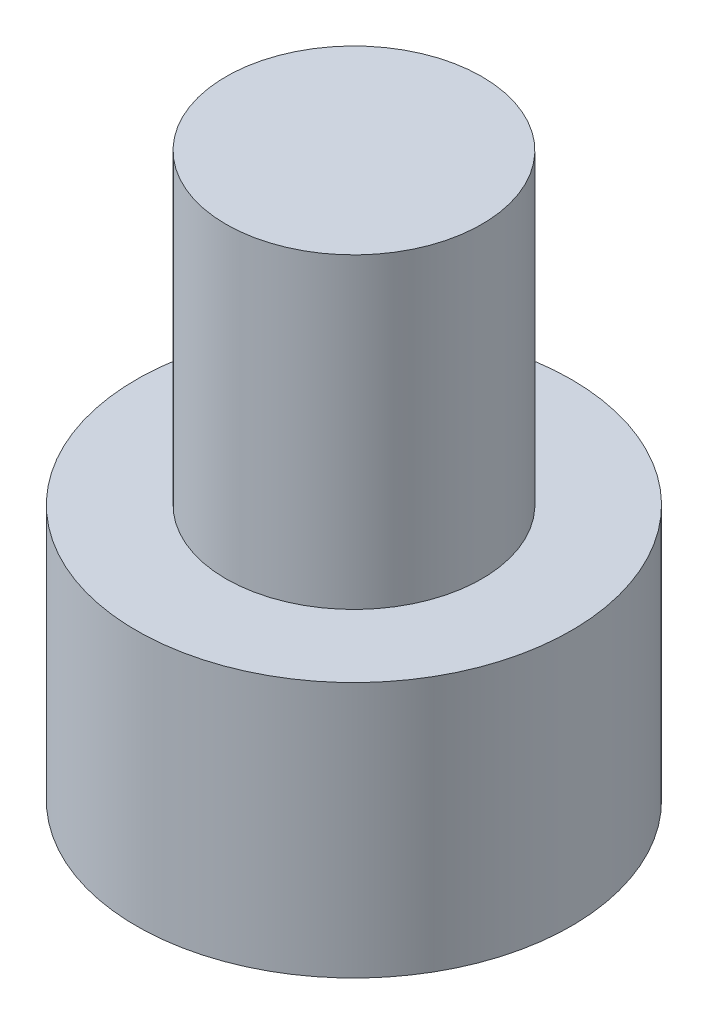
SolidWorks part; units mm, degrees
ref_plane "前视基准面" through (0, 0, 0) normal (0, 0, 1) x (1, 0, 0)
ref_plane "上视基准面" through (0, 0, 0) normal (0, 1, 0) x (1, 0, 0)
ref_plane "右视基准面" through (0, 0, 0) normal (1, 0, 0) x (0, 0, -1)
other "Configuration Table"
sketch "草图1" plane through (0, 0, 0) normal (0, 1, 0) x (1, 0, 0)
  circle A0 centre (0, 0) radius 2.5
  dimension "D1" = 5
extrude "凸台-拉伸1" add sketch "草图1" along normal blind 6
sketch "草图2" plane through (0, 0, 0) normal (0, -1, 0) x (1, 0, 0)
  circle A0 centre (0, 0) radius 4.25
  dimension "D1" = 8.5
extrude "凸台-拉伸2" add sketch "草图2" along normal blind 5
sketch "草图3" plane through (0, -5, 0) normal (0, -1, 0) x (1, 0, 0)
  line L1 (2.3094, 0) -> (1.1547, 2)
  line L2 (1.1547, 2) -> (-1.1547, 2)
  line L3 (-1.1547, 2) -> (-2.3094, 0)
  line L4 (-2.3094, 0) -> (-1.1547, -2)
  line L5 (-1.1547, -2) -> (1.1547, -2)
  line L6 (1.1547, -2) -> (2.3094, 0)
  circle A0 centre (0, 0) radius 2 construction
  dimension "D1" = 4
extrude "切除-拉伸1" cut sketch "草图3" against normal blind 1
